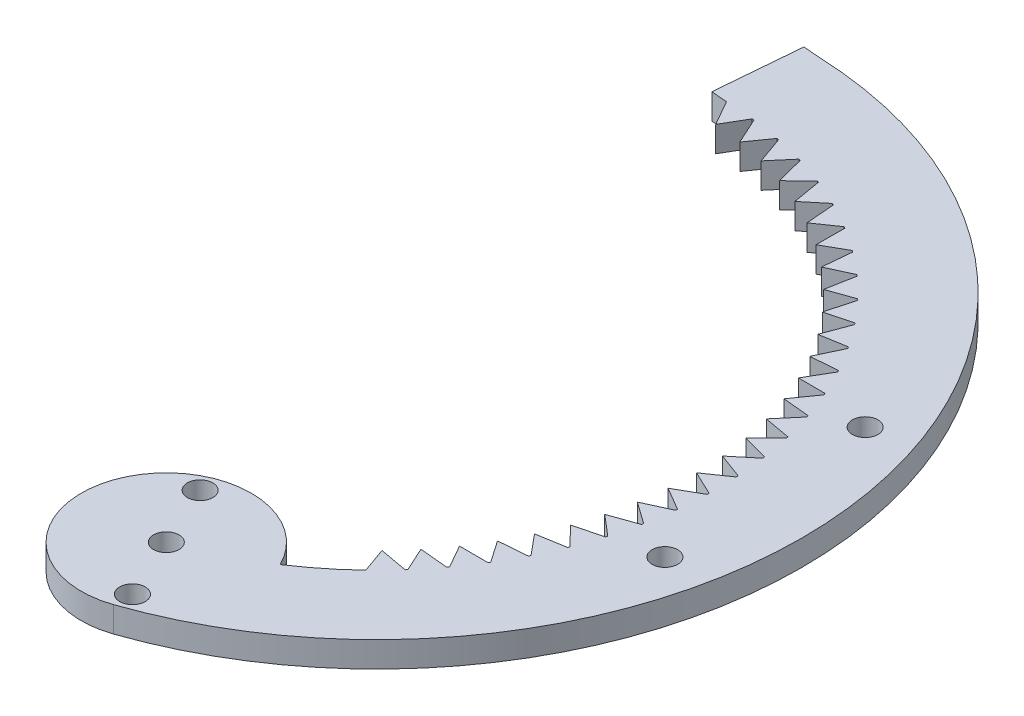
SolidWorks part; units mm, degrees
ref_plane "前视基准面" through (0, 0, 0) normal (0, 0, 1) x (1, 0, 0)
ref_plane "上视基准面" through (0, 0, 0) normal (0, 1, 0) x (1, 0, 0)
ref_plane "右视基准面" through (0, 0, 0) normal (1, 0, 0) x (0, 0, -1)
sketch "草图1" plane through (0, 0, 0) normal (0, 1, 0) x (1, 0, 0)
  line L0 (-22.706, 22.2911) -> (-18.1539, 75.324) construction
  line L1 (-1.2848, 20.4524) -> (-44.7839, 24.1861) construction
  line L58 (-17.4697, 83.2947) -> (-4.2812, 82.1627) construction
  line L59 (-11.9198, 77.7934) -> (-10.249, 74.8606)
  line L60 (-10.249, 74.8606) -> (-8.6651, 77.5678)
  line L62 (-7.0304, 74.475) -> (-5.2166, 77.0339)
  line L63 (-8.4393, 77.5422) -> (-7.0304, 74.475)
  line L64 (-3.8577, 73.8103) -> (-1.8278, 76.2014)
  line L65 (-4.9939, 76.9887) -> (-3.8577, 73.8103)
  line L66 (-0.7551, 72.8717) -> (1.4756, 75.0768)
  line L67 (-1.6099, 76.137) -> (-0.7551, 72.8717)
  line L68 (2.254, 71.6662) -> (4.6683, 73.6685)
  line L69 (1.687, 74.9937) -> (2.254, 71.6662)
  line L70 (5.1466, 70.2031) -> (7.7262, 71.9874)
  line L71 (4.8717, 73.5673) -> (5.1466, 70.2031)
  line L72 (7.9006, 68.4934) -> (10.6259, 70.0461)
  line L73 (7.92, 71.8688) -> (7.9006, 68.4934)
  line L74 (10.4951, 66.5503) -> (13.3454, 67.8594)
  line L75 (10.8087, 69.911) -> (10.4951, 66.5503)
  line L76 (12.9104, 64.3883) -> (15.864, 65.4441)
  line L77 (13.5157, 67.709) -> (12.9104, 64.3883)
  line L78 (15.1281, 62.0241) -> (18.1624, 62.8185)
  line L79 (16.0205, 65.2794) -> (15.1281, 62.0241)
  line L80 (17.1313, 59.4756) -> (20.2233, 60.0025)
  line L81 (18.304, 62.6407) -> (17.1313, 59.4756)
  line L82 (18.9048, 56.7622) -> (22.0309, 57.0176)
  line L83 (20.3489, 59.8131) -> (18.9048, 56.7622)
  line L84 (20.435, 53.9046) -> (23.5715, 53.8865)
  line L85 (22.1395, 56.818) -> (20.435, 53.9046)
  line L86 (21.7103, 50.9245) -> (24.8333, 50.6331)
  line L87 (23.6622, 53.6782) -> (21.7103, 50.9245)
  line L88 (22.7211, 47.8445) -> (25.8068, 47.2821)
  line L89 (24.9056, 50.4177) -> (22.7211, 47.8445)
  line L90 (23.4596, 44.6882) -> (26.4845, 43.859)
  line L91 (25.86, 47.0612) -> (23.4596, 44.6882)
  line L92 (23.9201, 41.4796) -> (26.8613, 40.3899)
  line L93 (26.5183, 43.6343) -> (23.9201, 41.4796)
  line L94 (24.0993, 38.243) -> (26.9343, 36.9011)
  line L95 (26.8753, 40.1631) -> (24.0993, 38.243)
  line L96 (23.9957, 35.0031) -> (26.703, 33.4192)
  line L97 (26.9285, 36.6739) -> (23.9957, 35.0031)
  line L98 (23.6101, 31.7845) -> (26.169, 29.9707)
  line L99 (26.6774, 33.1934) -> (23.6101, 31.7845)
  line L100 (22.9455, 28.6119) -> (25.3366, 26.5819)
  line L101 (26.1239, 29.748) -> (22.9455, 28.6119)
  line L102 (22.0069, 25.5092) -> (24.2119, 23.2786)
  line L103 (25.2722, 26.364) -> (22.0069, 25.5092)
  line L104 (20.8014, 22.5001) -> (22.8037, 20.0858)
  line L154 (24.1288, 23.0671) -> (20.8014, 22.5001)
  line L155 (19.3383, 19.6076) -> (21.1225, 17.0279)
  line L156 (22.7024, 19.8824) -> (19.3383, 19.6076)
  line L157 (17.6286, 16.8535) -> (19.1812, 14.1282)
  line L158 (21.0039, 16.8341) -> (17.6286, 16.8535)
  line L159 (15.6854, 14.259) -> (16.9946, 11.4087)
  line L160 (19.0462, 13.9455) -> (15.6854, 14.259)
  line L161 (13.5235, 11.8437) -> (14.5793, 8.8902)
  line L162 (16.8441, 11.2384) -> (13.5235, 11.8437)
  line L163 (-13.0554, 37.8095) -> (-10.249, 74.8606) construction
  line L164 (-13.0554, 37.8095) -> (-7.0304, 74.475) construction
  line L165 (-11.0635, 87.7698) -> (-12.9469, 87.9315)
  line L166 (-11.9198, 77.7934) -> (-13.8032, 77.955)
  line L167 (-16.7856, 91.2654) -> (-15.0307, 111.7093) construction
  line L168 (-12.9425, 87.9833) -> (-13.7977, 78.02) construction
  line L169 (-12.9469, 87.9315) -> (-13.8032, 77.955)
  arc A26 (8.9703, 4.4198) -> (14.5793, 8.8902) centre (-13.0554, 37.8095) ccw
  arc A27 (-8.4393, 77.5422) -> (-8.6651, 77.5678) centre (-13.0554, 37.8095) ccw
  arc A28 (-4.9939, 76.9887) -> (-5.2166, 77.0339) centre (-13.0554, 37.8095) ccw
  arc A29 (-1.6099, 76.137) -> (-1.8278, 76.2014) centre (-13.0554, 37.8095) ccw
  arc A30 (1.687, 74.9937) -> (1.4756, 75.0768) centre (-13.0554, 37.8095) ccw
  arc A31 (4.8717, 73.5673) -> (4.6683, 73.6685) centre (-13.0554, 37.8095) ccw
  arc A32 (7.92, 71.8688) -> (7.7262, 71.9874) centre (-13.0554, 37.8095) ccw
  arc A33 (10.8087, 69.911) -> (10.6259, 70.0461) centre (-13.0554, 37.8095) ccw
  arc A34 (13.5157, 67.709) -> (13.3454, 67.8594) centre (-13.0554, 37.8095) ccw
  arc A35 (16.0205, 65.2794) -> (15.864, 65.4441) centre (-13.0554, 37.8095) ccw
  arc A36 (18.304, 62.6407) -> (18.1624, 62.8185) centre (-13.0554, 37.8095) ccw
  arc A37 (20.3489, 59.8131) -> (20.2233, 60.0025) centre (-13.0554, 37.8095) ccw
  arc A38 (22.1395, 56.818) -> (22.0309, 57.0176) centre (-13.0554, 37.8095) ccw
  arc A39 (23.6622, 53.6782) -> (23.5715, 53.8865) centre (-13.0554, 37.8095) ccw
  arc A40 (24.9056, 50.4177) -> (24.8333, 50.6331) centre (-13.0554, 37.8095) ccw
  arc A41 (25.86, 47.0612) -> (25.8068, 47.2821) centre (-13.0554, 37.8095) ccw
  arc A42 (26.5183, 43.6343) -> (26.4845, 43.859) centre (-13.0554, 37.8095) ccw
  arc A64 (8.9703, 4.4198) -> (3.2638, -9.4524) centre (0, 0) ccw
  circle A65 centre (0, 0) radius 1.5
  arc A66 (26.8753, 40.1631) -> (26.8613, 40.3899) centre (-13.0554, 37.8095) ccw
  arc A67 (26.9285, 36.6739) -> (26.9343, 36.9011) centre (-13.0554, 37.8095) ccw
  arc A70 (26.6774, 33.1934) -> (26.703, 33.4192) centre (-13.0554, 37.8095) ccw
  arc A71 (26.1239, 29.748) -> (26.169, 29.9707) centre (-13.0554, 37.8095) ccw
  arc A72 (25.2722, 26.364) -> (25.3366, 26.5819) centre (-13.0554, 37.8095) ccw
  arc A73 (24.1288, 23.0671) -> (24.2119, 23.2786) centre (-13.0554, 37.8095) ccw
  arc A74 (22.7024, 19.8824) -> (22.8037, 20.0858) centre (-13.0554, 37.8095) ccw
  arc A75 (21.0039, 16.8341) -> (21.1225, 17.0279) centre (-13.0554, 37.8095) ccw
  arc A76 (19.0462, 13.9455) -> (19.1812, 14.1282) centre (-13.0554, 37.8095) ccw
  arc A77 (16.8441, 11.2384) -> (16.9946, 11.4087) centre (-13.0554, 37.8095) ccw
  arc A137 (3.2638, -9.4524) -> (-11.0635, 87.7698) centre (-13.0554, 37.8095) ccw
  dimension "D1" = 3
  dimension "D2" = 50
  dimension "D6" = 40
  dimension "D4" = 10
  dimension "D3" = 43.6591
  dimension "D5" = 16
  dimension "D7" = 60
  dimension "D8" = 5
  dimension "D9" = 37.1572
  dimension "D10" = 27
  dimension "D11" = 21.5
extrude "凸台-拉伸1" add sketch "草图1" along normal blind 3
sketch "草图2" plane through (0, 3, 0) normal (0, 1, 0) x (1, 0, 0)
  circle A2 centre (-3.3072, 7.2844) radius 1.5
  circle A3 centre (3.3072, -7.2844) radius 1.5
  dimension "D1" = 8
  dimension "D2" = 8
extrude "切除-拉伸1" cut sketch "草图2" against normal blind 35
sketch "草图3" plane through (0, 3, 0) normal (0, 1, 0) x (1, 0, 0)
  circle A0 centre (30.8195, 27.8095) radius 1.5
  circle A1 centre (29.371, 52.8095) radius 1.5
  arc A2 (3.2638, -9.4524) -> (-11.0635, 87.7698) centre (-13.0554, 37.8095) ccw construction
  dimension "D1" = 3
  dimension "D2" = 45
  dimension "D3" = 10
  dimension "D4" = 45
  dimension "D5" = 25
extrude "切除-拉伸2" cut sketch "草图3" against normal blind 10
